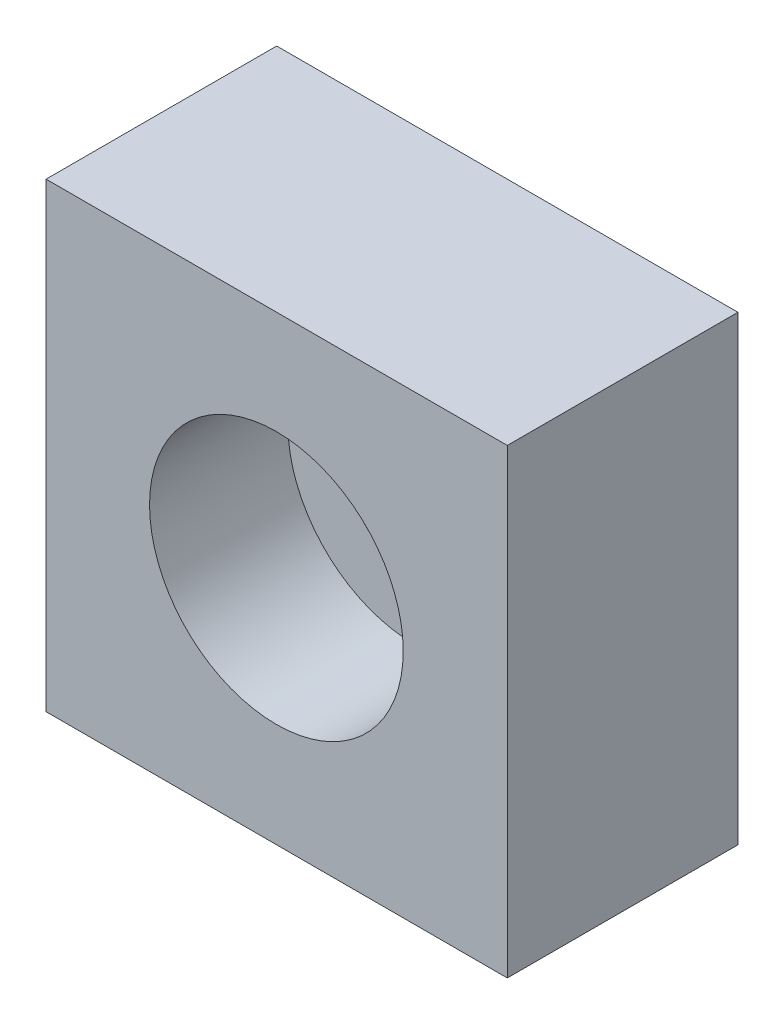
SolidWorks part; units mm, degrees
ref_plane "前视基准面" through (0, 0, 0) normal (0, 0, 1) x (1, 0, 0)
ref_plane "上视基准面" through (0, 0, 0) normal (0, 1, 0) x (1, 0, 0)
ref_plane "右视基准面" through (0, 0, 0) normal (1, 0, 0) x (0, 0, -1)
other "Configuration Table"
sketch "草图1" plane through (0, 0, 0) normal (0, 0, 1) x (1, 0, 0)
  line L1 (0, 0) -> (20, 0)
  line L2 (0, 0) -> (0, 20)
  line L3 (0, 20) -> (20, 20)
  line L4 (20, 0) -> (20, 20)
extrude "BaseBox" add sketch "草图1" along normal blind 10
hole_wizard "Hole_cb_iso_socketcap_m6" positions "草图3" profile "草图2" counterbore size "M6" standard "ISO" end condition through all
sketch "草图3" plane through (0, 0, 10) normal (0, 0, 1) x (1, 0, 0)
  point P0 (9.9865, 10.0143)
sketch "草图2" plane through (9.9865, 10.0143, 10) normal (1, 0, 0) x (0, -1, 0)
  line L0 (0, 0) -> (0, 10)
  line L1 (0, 10) -> (3, 10)
  line L3 (3, 10) -> (3, 6)
  line L4 (3, 6) -> (5.5, 6)
  line L5 (5.5, 6) -> (5.5, 0)
  line L7 (5.5, 0) -> (0, 0)
  line L11 (0, -6.35) -> (0, 107.95) construction
  dimension "通孔孔直径" = 6
  dimension "通孔孔深度" = 10
  dimension "柱形沉头孔直径" = 11
  dimension "柱形沉头孔深度" = 6
